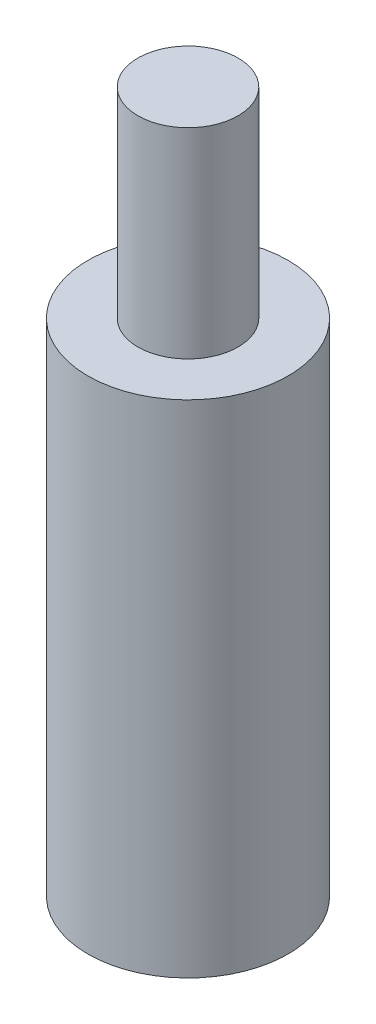
SolidWorks part; units mm, degrees
ref_plane "Front Plane" through (0, 0, 0) normal (0, 0, 1) x (1, 0, 0)
ref_plane "Top Plane" through (0, 0, 0) normal (0, 1, 0) x (1, 0, 0)
ref_plane "Right Plane" through (0, 0, 0) normal (1, 0, 0) x (0, 0, -1)
sketch "Sketch1" plane through (0, 0, 0) normal (0, 1, 0) x (1, 0, 0)
  circle A0 centre (0, 0) radius 1
  circle A1 centre (0, 0) radius 2
  dimension "D1" = 4
  dimension "D2" = 2
extrude "Boss-Extrude1" add sketch "Sketch1" along normal blind 10
sketch "Sketch2" plane through (0, 10, 0) normal (0, 1, 0) x (1, 0, 0)
  circle A0 centre (0, 0) radius 1
extrude "Boss-Extrude2" add sketch "Sketch2" along normal blind 4 separate body
